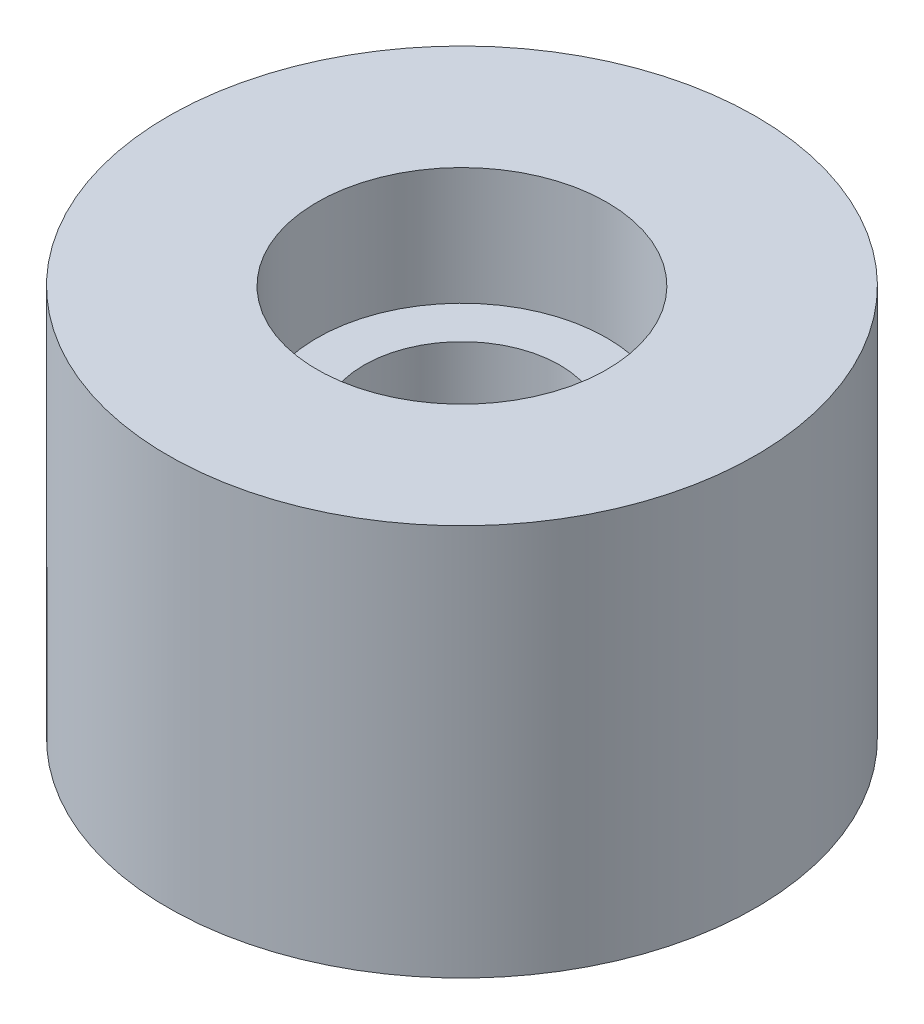
SolidWorks part; units mm, degrees
ref_plane "Ebene vorne" through (0, 0, 0) normal (0, 0, 1) x (1, 0, 0)
ref_plane "Ebene oben" through (0, 0, 0) normal (0, 1, 0) x (1, 0, 0)
ref_plane "Ebene rechts" through (0, 0, 0) normal (1, 0, 0) x (0, 0, -1)
sketch "Sketch1" plane through (0, 0, 0) normal (0, 0, 1) x (1, 0, 0)
  line L0 (0, -6.6295) -> (0, 11.8219) construction
  line L1 (-3.7, 0) -> (-7.5, 0)
  line L2 (-7.5, 0) -> (-7.5, 0.5)
  line L3 (-7.5, 10) -> (-3.7, 10)
  line L4 (-3.7, 10) -> (-3.7, 7)
  line L5 (-3.7, 3) -> (-3.7, 0)
  line L6 (-7.5, 5.5) -> (-7.5, 0.5)
  line L7 (-7.5, 5.5) -> (-7.5, 10)
  line L8 (-9.5865, 5) -> (-0.4874, 5) construction
  line L10 (-3.7, 3) -> (-2.5, 3)
  line L11 (-2.5, 3) -> (-2.5, 7)
  line L12 (-2.5, 7) -> (-3.7, 7)
  dimension "D1" = 7.4
  dimension "D2" = 3
  dimension "D3" = 5
  dimension "D5" = 15
  dimension "D8" = 4
revolve "Revolve1" add sketch "Sketch1" angle 360 about L0
